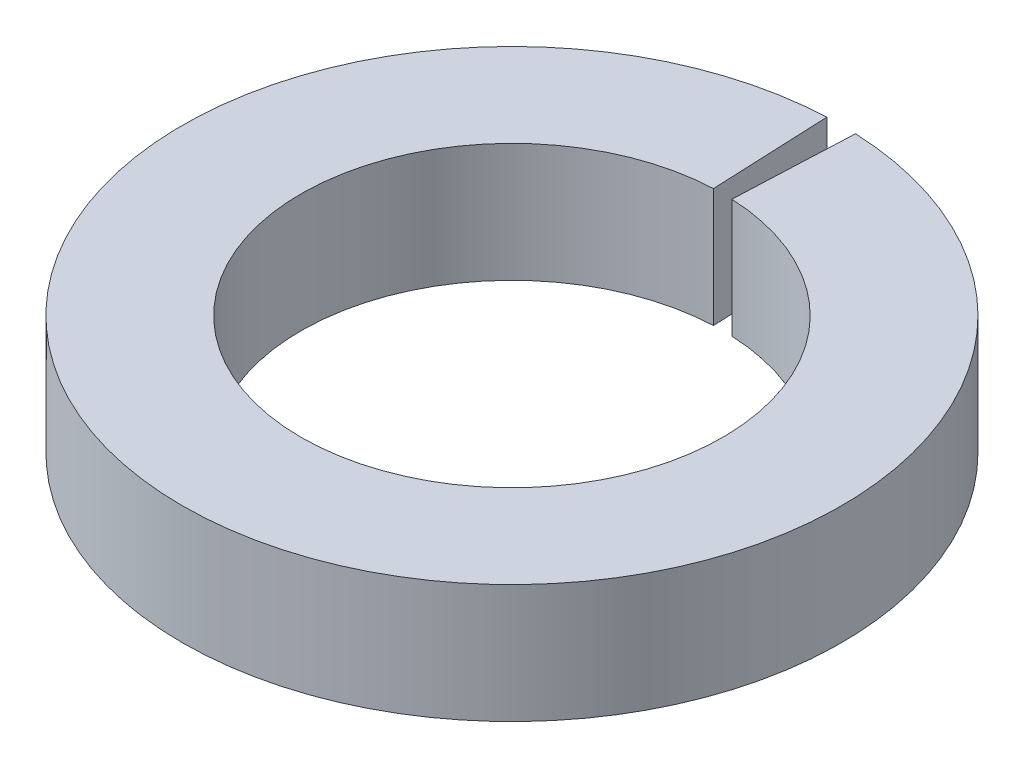
SolidWorks part; units mm, degrees
ref_plane "Front Plane" through (0, 0, 0) normal (0, 0, 1) x (1, 0, 0)
ref_plane "Top Plane" through (0, 0, 0) normal (0, 1, 0) x (1, 0, 0)
ref_plane "Right Plane" through (0, 0, 0) normal (1, 0, 0) x (0, 0, -1)
sketch "Sketch1" plane through (0, 0, 0) normal (0, 1, 0) x (1, 0, 0)
  line L0 (-0.0698, 1.5985) -> (-0.109, 2.4976)
  line L1 (0, 0) -> (-0.109, 2.4976) construction
  line L2 (0.109, 2.4976) -> (0, 0) construction
  line L3 (0.109, 2.4976) -> (0.0698, 1.5985)
  line L4 (0, 0) -> (0, 4.0578) construction
  arc A0 (-0.0698, 1.5985) -> (0.0698, 1.5985) centre (0, 0) ccw
  arc A1 (-0.109, 2.4976) -> (0.109, 2.4976) centre (0, 0) ccw
  point P6 (-0.3164, 2.4691)
  point P9 (0, 0)
  dimension "D1" = 3.2
  dimension "D2" = 5
  dimension "D3" = 0.9
  dimension "D4" = 5
extrude "Boss-Extrude1" add sketch "Sketch1" along normal blind 0.9
